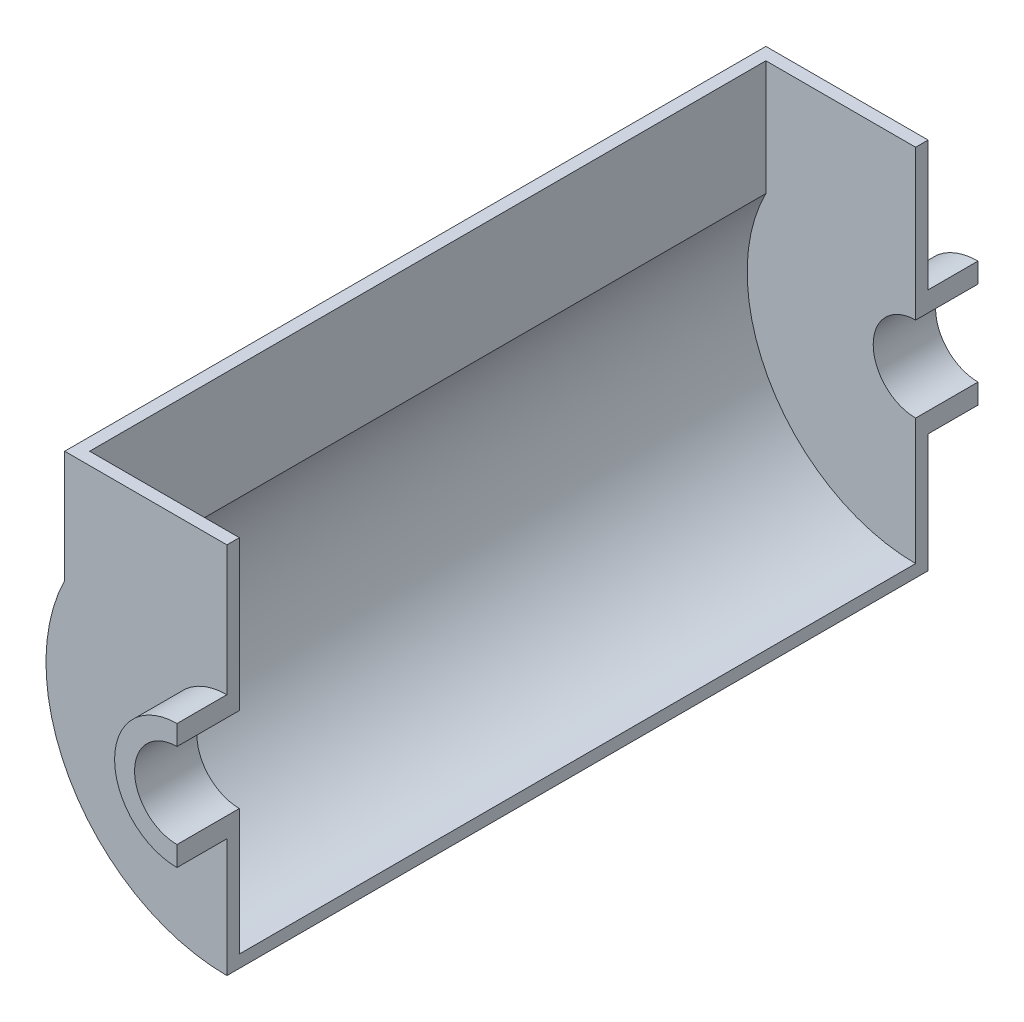
SolidWorks part; units mm, degrees
ref_plane "Front Plane" through (0, 0, 0) normal (0, 0, 1) x (1, 0, 0)
ref_plane "Top Plane" through (0, 0, 0) normal (0, 1, 0) x (1, 0, 0)
ref_plane "Right Plane" through (0, 0, 0) normal (1, 0, 0) x (0, 0, -1)
sketch "Sketch2" plane through (0, 0, 0) normal (0, 0, 1) x (1, 0, 0)
  line L0 (0, 25) -> (0, 17)
  line L1 (0, -17) -> (0, -25)
  arc A0 (0, 17) -> (0, -17) centre (0, 0) ccw
  arc A1 (0, 25) -> (0, -25) centre (0, 0) ccw
  dimension "D1" = 50
  dimension "D2" = 34
extrude "Boss-Extrude1" add sketch "Sketch2" along normal blind 20 and the other way blind 5
sketch "Sketch3" plane through (0, 0, 0) normal (0, 0, 1) x (1, 0, 0)
  line L0 (0, 25) -> (0, 77)
  line L1 (0, 77) -> (-65, 77)
  line L2 (-65, 77) -> (-65, 32.1131)
  line L3 (0, -25) -> (0, -72.5)
  arc A0 (0, 25) -> (0, -25) centre (0, 0) ccw construction
  arc A1 (0, 25) -> (0, -25) centre (0, 0) ccw
  arc A2 (-65, 32.1131) -> (0, -72.5) centre (0, 0) ccw
  dimension "D3" = 72.5
  dimension "D1" = 52
  dimension "D2" = 65
extrude "Boss-Extrude2" add sketch "Sketch3" against normal blind 5
ref_plane "Plane1" through (0, 0, -140.5) normal (0, 0, 1) x (1, 0, 0)
mirror "Mirror3" about plane through (0, 0, -140.5) normal (0, 0, 1) of bodies 102
sketch "Sketch4" plane through (0, 0, -5) normal (0, 0, -1) x (-1, 0, 0)
  line L0 (65, 77) -> (65, 32.1131) construction
  line L1 (65, 77) -> (65, 32.1131)
  line L2 (60, 77) -> (60, 30.9233)
  line L3 (65, 77) -> (60, 77)
  line L4 (0, -72.5) -> (0, -67.5)
  arc A0 (0, -72.5) -> (65, 32.1131) centre (0, 0) ccw construction
  arc A1 (0, -72.5) -> (65, 32.1131) centre (0, 0) ccw
  arc A2 (0, -67.5) -> (60, 30.9233) centre (0, 0) ccw
  dimension "D1" = 5
extrude "Boss-Extrude3" add sketch "Sketch4" along normal up to surface (271 mm away) up to face at (-29.3468, 15.924, -276)
